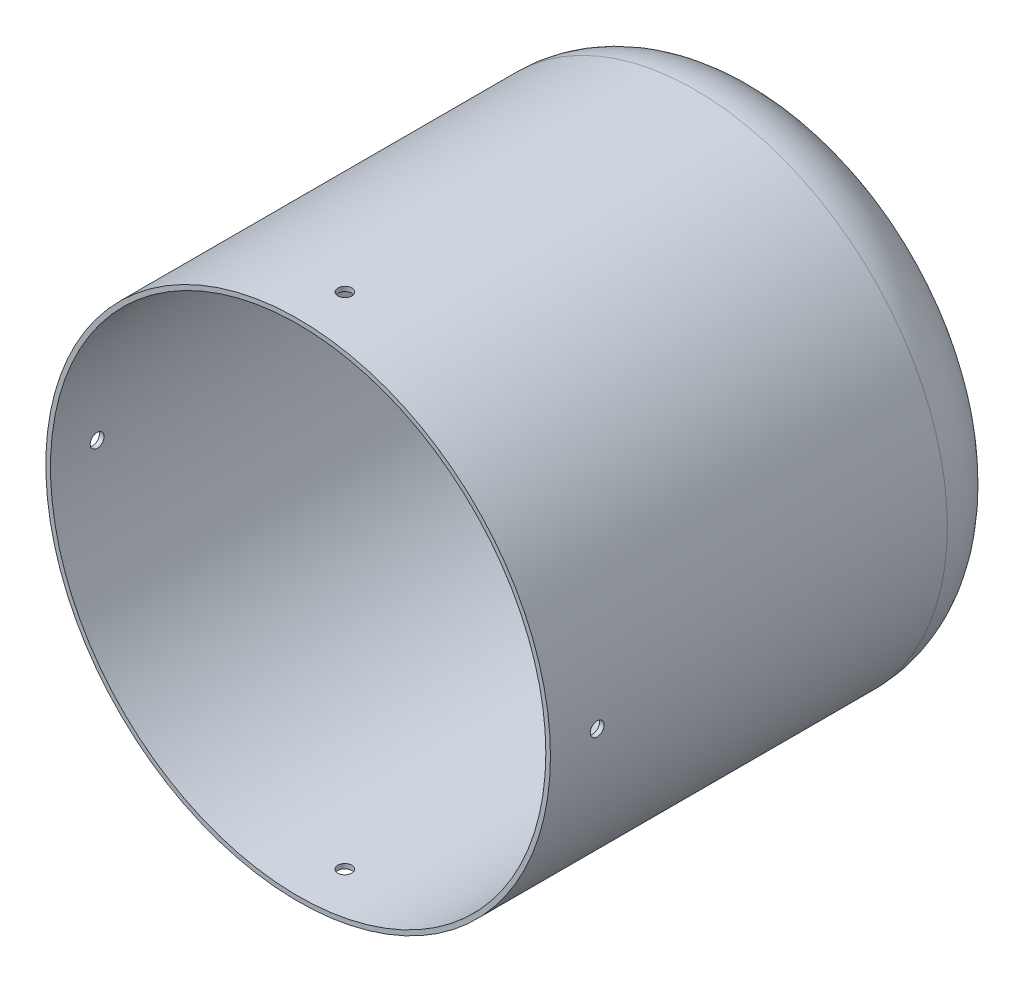
SolidWorks part; units mm, degrees
ref_plane "Plan1" through (0, 0, 0) normal (0, 0, 1) x (1, 0, 0)
ref_plane "Plan2" through (0, 0, 0) normal (0, 1, 0) x (1, 0, 0)
ref_plane "Plan3" through (0, 0, 0) normal (1, 0, 0) x (0, 0, -1)
sketch "Esquisse1" plane through (0, 0, 0) normal (1, 0, 0) x (0, 0, -1)
  line L1 (-74.9267, 0) -> (127.0979, 0) construction
  line L4 (112, 34.4) -> (112, 42.5)
  line L5 (112, 42.5) -> (111, 42.5)
  line L6 (112, 34.4) -> (110, 34.4)
  line L7 (108.5, 35.5) -> (108.5, 41.15)
  line L8 (108.5, 41.15) -> (105.7, 41.15)
  line L9 (105.7, 41.15) -> (105.7, 25.9975) construction
  line L10 (110, 34.4) -> (110, 35.5)
  line L11 (110, 35.5) -> (108.5, 35.5)
  line L12 (95.5, 54.5) -> (-7, 54.5)
  line L13 (93.35, 53.5) -> (-7, 53.5)
  line L14 (-7, 53.5) -> (-7, 54.5)
  arc A0 (95.5, 54.5) -> (111, 42.5) centre (95.5, 38.4896) cw
  arc A1 (93.35, 53.5) -> (105.7, 41.15) centre (93.35, 41.15) cw
  dimension "D2" = 34.4
  dimension "D3" = 102.5
  dimension "D4" = 68.8
  dimension "D5" = 85
  dimension "D6" = 1
  dimension "D7" = 109
  dimension "D8" = 3.5
  dimension "D10" = 82.3
  dimension "D11" = 2
  dimension "D12" = 71
  dimension "D14" = 6.3
  dimension "D15" = 2.8
revolve "Base-Révolution" add sketch "Esquisse1" angle 360 about L1
sketch "Esquisse2" plane through (0, 0, -108.5) normal (0, 0, 1) x (1, 0, 0)
  line L0 (0, 0) -> (0, 38) construction
  circle A0 centre (0, 38) radius 1.5
  circle A1 centre (19, 32.909) radius 1.5
  circle A2 centre (32.909, 19) radius 1.5
  circle A3 centre (38, 0) radius 1.5
  circle A4 centre (32.909, -19) radius 1.5
  circle A5 centre (19, -32.909) radius 1.5
  circle A6 centre (0, -38) radius 1.5
  circle A7 centre (-19, -32.909) radius 1.5
  circle A8 centre (-32.909, -19) radius 1.5
  circle A9 centre (-38, 0) radius 1.5
  circle A10 centre (-32.909, 19) radius 1.5
  circle A11 centre (-19, 32.909) radius 1.5
  dimension "D1" = 3
  dimension "D2" = 38
  dimension "D3" = 38
extrude "Enlèv. mat.-Extru.1" cut sketch "Esquisse2" against normal through all
sketch "Sketch3" plane through (0, 0, 0) normal (1, 0, 0) x (0, 0, -1)
ref_plane "Plane3" through (0, 0, 7) normal (0, 0, 1) x (1, 0, 0)
sketch "Sketch6" plane through (0, 0, 7) normal (0, 0, 1) x (1, 0, 0)
  circle A0 centre (0, 0) radius 53.5
  circle A1 centre (0, 0) radius 54.5
extrude "Cut-Extrude4" cut sketch "Sketch6" against normal blind 16.77 and the other way through all
sketch "Sketch7" plane through (0, 0, 0) normal (0, 1, 0) x (1, 0, 0)
  line L0 (0, -7) -> (0, 32.4562)
  line L1 (-55, -7) -> (55, -7) construction
  line L2 (0, 9.77) -> (0, 19.86)
  line L3 (-54.5, 9.77) -> (54.5, 9.77) construction
  circle A2 centre (0, 19.86) radius 1.5
  dimension "D1" = 3
  dimension "D2" = 10.09
extrude "Cut-Extrude5" cut sketch "Sketch7" against normal through all both and the other way through all
sketch "Sketch8" plane through (0, 0, 0) normal (1, 0, 0) x (0, 0, -1)
  line L0 (9.77, 0) -> (19.86, 0)
  line L1 (9.77, 54.5) -> (9.77, -54.5) construction
  circle A0 centre (19.86, 0) radius 1.5
  dimension "D2" = 3
  dimension "D1" = 10.09
extrude "Cut-Extrude6" cut sketch "Sketch8" against normal through all both and the other way through all contours A0
